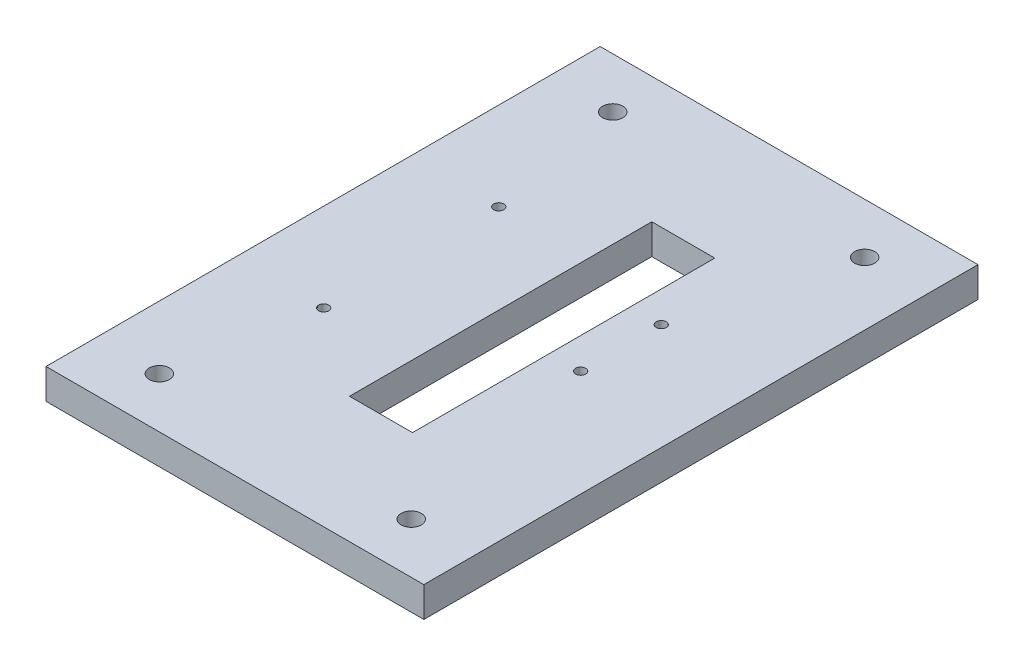
SolidWorks part; units mm, degrees
ref_plane "Front Plane" through (0, 0, 0) normal (0, 0, 1) x (1, 0, 0)
ref_plane "Top Plane" through (0, 0, 0) normal (0, 1, 0) x (1, 0, 0)
ref_plane "Right Plane" through (0, 0, 0) normal (1, 0, 0) x (0, 0, -1)
sketch "Sketch1" plane through (0, 0, 0) normal (0, 1, 0) x (1, 0, 0)
  line L0 (-40, 34.75) -> (-40, -34.75) construction
  line L1 (75, 110) -> (-75, 110)
  line L2 (75, 110) -> (75, -110)
  line L3 (75, -110) -> (-75, -110)
  line L4 (-75, 110) -> (-75, -110)
  line L5 (75, 110) -> (-75, -110) construction
  line L6 (75, -110) -> (-75, 110) construction
  line L7 (0, 0) -> (-40, 0) construction
  line L13 (-4.5, -60) -> (20.5, -60)
  line L14 (-4.5, -60) -> (-4.5, 60)
  line L15 (-4.5, 60) -> (20.5, 60)
  line L16 (20.5, -60) -> (20.5, 60)
  line L17 (-4.5, -60) -> (20.5, 60) construction
  line L18 (-4.5, 60) -> (20.5, -60) construction
  line L19 (-50, 90) -> (50, 90)
  line L20 (-50, 90) -> (-50, -90)
  line L21 (-50, -90) -> (50, -90)
  line L22 (50, 90) -> (50, -90)
  line L23 (-50, 90) -> (50, -90) construction
  line L24 (-50, -90) -> (50, 90) construction
  circle A0 centre (-40, 34.75) radius 2
  circle A1 centre (-40, -34.75) radius 2
  circle A2 centre (-50, 90) radius 4
  circle A3 centre (50, 90) radius 4
  circle A4 centre (-50, -90) radius 4
  circle A5 centre (50, -90) radius 4
  point P0 (0, 0)
  point P10 (-40, 0)
  point P13 (8, 0)
  dimension "D5" = 4
  dimension "D6" = 4
  dimension "D1" = 220
  dimension "D2" = 150
  dimension "D3" = 69.5
  dimension "D4" = 40
  dimension "D7" = 25
  dimension "D8" = 120
  dimension "D9" = 8
  dimension "D10" = 180
  dimension "D11" = 100
extrude "Boss-Extrude1" add sketch "Sketch1" along normal blind 12 contours L1 L4 L3 L2 A5 L21 A4 L20 A2 L19 A3 L22 | A5 L22 A3 L19 A2 L20 A4 L21 A1 A0 L16 L13 L14 L15
sketch "Sketch2" plane through (0, 12, 0) normal (0, 1, 0) x (1, 0, 0)
  circle A0 centre (32.75, 26.5) radius 2
  circle A1 centre (32.75, -5.5) radius 2
extrude "Cut-Extrude1" cut sketch "Sketch2" against normal up to surface (12 mm away) up to face at (50, 0, 94)
